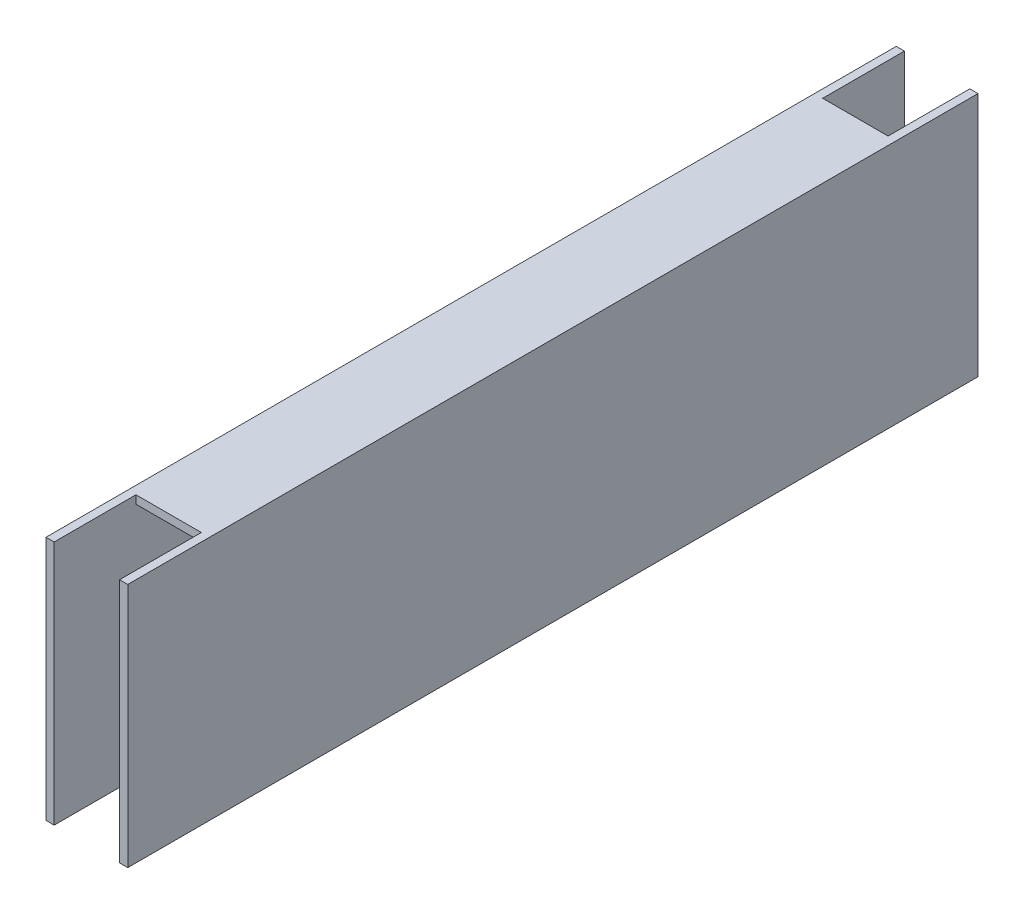
SolidWorks part; units mm, degrees
ref_plane "Front Plane" through (0, 0, 0) normal (0, 0, 1) x (1, 0, 0)
ref_plane "Top Plane" through (0, 0, 0) normal (0, 1, 0) x (1, 0, 0)
ref_plane "Right Plane" through (0, 0, 0) normal (1, 0, 0) x (0, 0, -1)
sketch "Sketch1" plane through (0, 0, 0) normal (0, 1, 0) x (1, 0, 0)
  line L2 (-25, 0) -> (25, 0)
  line L3 (-25, 0) -> (-25, 420)
  line L4 (-25, 420) -> (25, 420)
  line L5 (25, 420) -> (25, 0)
  dimension "D1" = 50
  dimension "D2" = 420
extrude "Boss-Extrude1" add sketch "Sketch1" along normal blind 150
sketch "Sketch3" plane through (0, 0, 0) normal (0, 0, 1) x (1, 0, 0)
  line L0 (25, 150) -> (25, 0) construction
  line L1 (-25, 0) -> (25, 0) construction
  line L7 (-20, 75) -> (-20, 5)
  line L8 (-20, 5) -> (20, 5)
  line L9 (20, 5) -> (20, 145)
  line L10 (20, 145) -> (-20, 145)
  line L11 (-20, 145) -> (-20, 75)
  dimension "D1" = 140
  dimension "D2" = 40
  dimension "D3" = 5
  dimension "D4" = 5
extrude "Cut-Extrude1" cut sketch "Sketch3" against normal through all
sketch "Sketch4" plane through (0, 0, 0) normal (0, 0, 1) x (1, 0, 0)
  line L1 (-25, 0) -> (25, 0) construction
  line L2 (20, 0) -> (20, 150)
  line L3 (-25, 150) -> (25, 150) construction
  line L4 (20, 150) -> (25, 150)
  line L5 (25, 150) -> (25, 0)
  line L6 (25, 0) -> (20, 0)
extrude "Boss-Extrude2" add sketch "Sketch4" along normal blind 50
sketch "Sketch5" plane through (0, 0, 0) normal (0, 0, 1) x (1, 0, 0)
  line L1 (-25, 0) -> (20, 0) construction
  line L2 (-20, 0) -> (-25, 0)
  line L3 (-25, 0) -> (-25, 150)
  line L4 (-25, 150) -> (-20, 150)
  line L5 (-25, 150) -> (20, 150) construction
  line L7 (-20, 150) -> (-20, 0)
extrude "Boss-Extrude3" add sketch "Sketch5" along normal blind 50
sketch "Sketch7" plane through (0, 0, -420) normal (0, 0, -1) x (-1, 0, 0)
  line L1 (-25, 150) -> (25, 150) construction
  line L2 (-20, 150) -> (-25, 150)
  line L3 (-25, 150) -> (-25, 0)
  line L4 (-25, 0) -> (-20, 0)
  line L5 (-20, 0) -> (-20, 150)
extrude "Boss-Extrude4" add sketch "Sketch7" along normal blind 50
sketch "Sketch8" plane through (0, 0, -420) normal (0, 0, -1) x (-1, 0, 0)
  line L0 (20, 150) -> (20, 0)
  line L1 (20, 0) -> (25, 0)
  line L2 (25, 0) -> (25, 150)
  line L3 (25, 150) -> (20, 150)
extrude "Boss-Extrude5" add sketch "Sketch8" along normal blind 50
